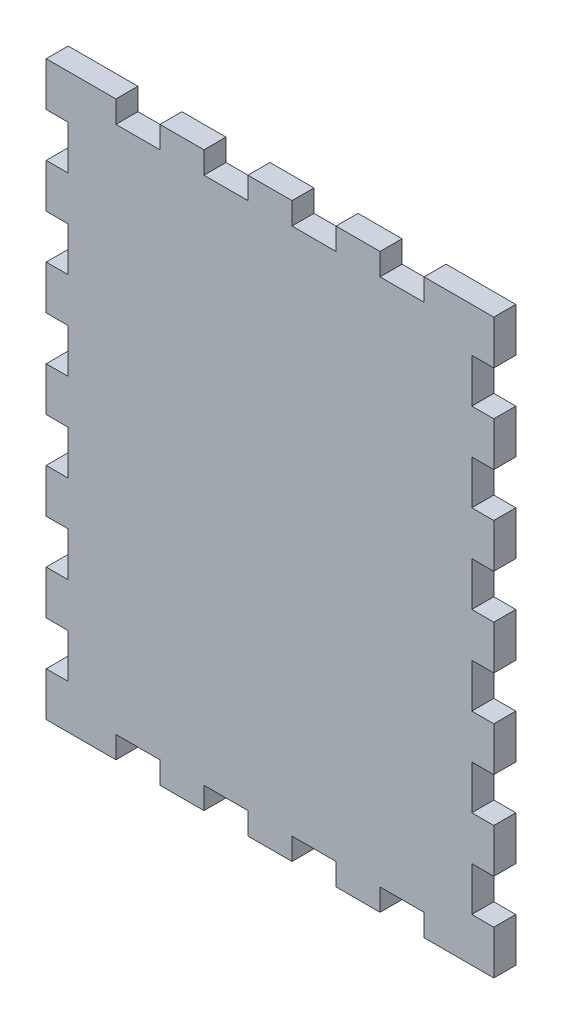
SolidWorks part; units mm, degrees
material "PMMA"
ref_plane "前视基准面" through (0, 0, 0) normal (0, 0, 1) x (1, 0, 0)
ref_plane "上视基准面" through (0, 0, 0) normal (0, 1, 0) x (1, 0, 0)
ref_plane "右视基准面" through (0, 0, 0) normal (1, 0, 0) x (0, 0, -1)
other "Configuration Table"
sketch "草图2" plane through (0, 0, 0) normal (0, 0, 1) x (1, 0, 0)
  line L0 (0, 81) -> (0, 75)
  line L1 (0, 75) -> (3, 75)
  line L2 (3, 75) -> (3, 69)
  line L3 (3, 69) -> (0, 69)
  line L4 (0, 69) -> (0, 63)
  line L5 (0, 63) -> (3, 63)
  line L6 (3, 63) -> (3, 57)
  line L7 (3, 57) -> (0, 57)
  line L8 (0, 57) -> (0, 51)
  line L9 (0, 51) -> (3, 51)
  line L10 (3, 51) -> (3, 45)
  line L11 (3, 45) -> (0, 45)
  line L12 (0, 45) -> (0, 39)
  line L13 (0, 39) -> (3, 39)
  line L14 (3, 39) -> (3, 33)
  line L15 (3, 33) -> (0, 33)
  line L16 (0, 33) -> (0, 27)
  line L17 (0, 27) -> (3, 27)
  line L18 (3, 27) -> (3, 21)
  line L19 (3, 21) -> (0, 21)
  line L20 (0, 21) -> (0, 15)
  line L21 (0, 15) -> (3, 15)
  line L22 (3, 15) -> (3, 9)
  line L23 (3, 9) -> (0, 9)
  line L24 (0, 9) -> (0, 3)
  line L25 (0, 3) -> (9.5, 3)
  line L26 (9.5, 3) -> (9.5, 6)
  line L27 (9.5, 6) -> (15.5, 6)
  line L28 (15.5, 6) -> (15.5, 3)
  line L29 (15.5, 3) -> (21.5, 3)
  line L30 (21.5, 3) -> (21.5, 6)
  line L31 (21.5, 6) -> (27.5, 6)
  line L32 (27.5, 6) -> (27.5, 3)
  line L33 (27.5, 3) -> (33.5, 3)
  line L34 (33.5, 3) -> (33.5, 6)
  line L35 (33.5, 6) -> (39.5, 6)
  line L36 (39.5, 6) -> (39.5, 3)
  line L37 (39.5, 3) -> (45.5, 3)
  line L38 (45.5, 3) -> (45.5, 6)
  line L39 (45.5, 6) -> (51.5, 6)
  line L40 (51.5, 6) -> (51.5, 3)
  line L41 (51.5, 3) -> (57.5, 3)
  line L42 (57.5, 3) -> (61, 3)
  line L43 (61, 3) -> (61, 9)
  line L44 (61, 9) -> (58, 9)
  line L45 (58, 9) -> (58, 15)
  line L46 (58, 15) -> (61, 15)
  line L47 (61, 15) -> (61, 21)
  line L48 (61, 21) -> (58, 21)
  line L49 (58, 21) -> (58, 27)
  line L50 (58, 27) -> (61, 27)
  line L51 (61, 27) -> (61, 33)
  line L52 (61, 33) -> (58, 33)
  line L53 (58, 33) -> (58, 39)
  line L54 (58, 39) -> (61, 39)
  line L55 (61, 39) -> (61, 45)
  line L56 (61, 45) -> (58, 45)
  line L57 (58, 45) -> (58, 51)
  line L58 (58, 51) -> (61, 51)
  line L59 (61, 51) -> (61, 57)
  line L60 (61, 57) -> (58, 57)
  line L61 (58, 57) -> (58, 63)
  line L62 (58, 63) -> (61, 63)
  line L63 (61, 63) -> (61, 69)
  line L64 (61, 69) -> (58, 69)
  line L65 (58, 69) -> (58, 75)
  line L66 (58, 75) -> (61, 75)
  line L67 (61, 75) -> (61, 81)
  line L68 (61, 81) -> (51.5, 81)
  line L69 (51.5, 81) -> (51.5, 78)
  line L70 (51.5, 78) -> (45.5, 78)
  line L71 (45.5, 78) -> (45.5, 81)
  line L72 (45.5, 81) -> (39.5, 81)
  line L73 (39.5, 81) -> (39.5, 78)
  line L74 (39.5, 78) -> (33.5, 78)
  line L75 (33.5, 78) -> (33.5, 81)
  line L76 (33.5, 81) -> (27.5, 81)
  line L77 (27.5, 81) -> (27.5, 78)
  line L78 (27.5, 78) -> (21.5, 78)
  line L79 (21.5, 78) -> (21.5, 81)
  line L80 (21.5, 81) -> (15.5, 81)
  line L81 (15.5, 81) -> (15.5, 78)
  line L82 (15.5, 78) -> (9.5, 78)
  line L83 (9.5, 78) -> (9.5, 81)
  line L84 (9.5, 81) -> (3.5, 81)
  line L85 (3.5, 81) -> (0, 81)
extrude "凸台-拉伸1" add sketch "草图2" along normal blind 3
